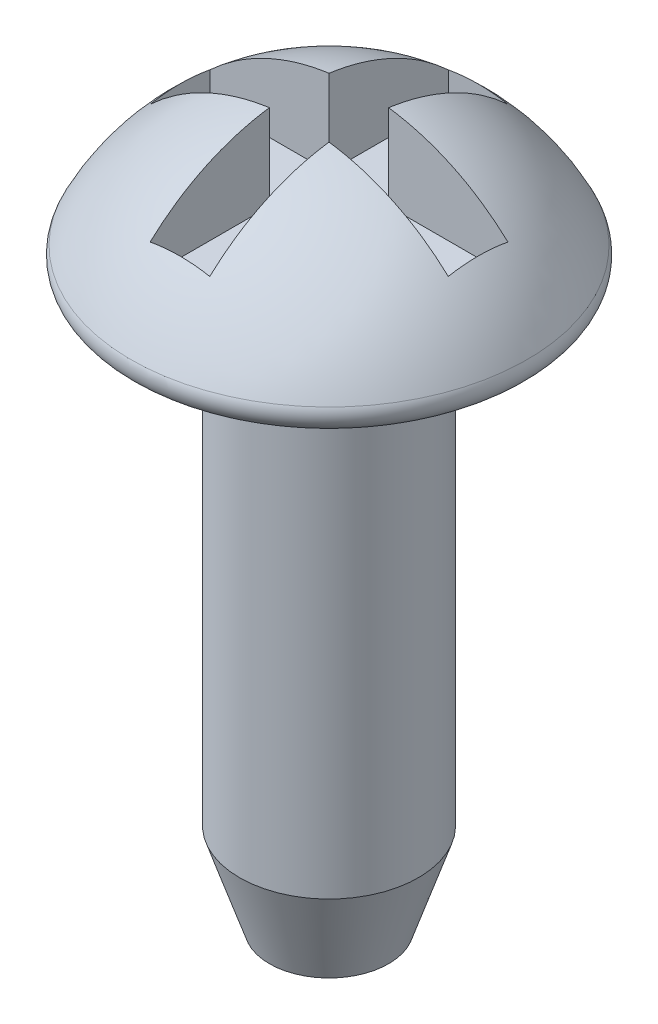
SolidWorks part; units mm, degrees
ref_plane "Front Plane" through (0, 0, 0) normal (0, 0, 1) x (1, 0, 0)
ref_plane "Top Plane" through (0, 0, 0) normal (0, 1, 0) x (1, 0, 0)
ref_plane "Right Plane" through (0, 0, 0) normal (1, 0, 0) x (0, 0, -1)
sketch "Sketch1" plane through (0, 0, 0) normal (0, 0, 1) x (1, 0, 0)
  line L0 (-1.5, 0) -> (-1.5, -8)
  line L1 (3.575, 0) -> (-3.575, 0) construction
  line L2 (-1.5, -8) -> (-1, -9.5)
  line L3 (-1, -9.5) -> (0, -9.5)
  line L4 (0, -3.575) -> (0, 3.575) construction
  line L5 (0, -2.514) -> (0, -4.9556) construction
  line L6 (0, -9.5) -> (0, 2.5)
  line L7 (-1.5, 0) -> (-3.5, 0)
  arc A0 (-3.5, 0) -> (0, 2.5) centre (0, -1.2) cw
  dimension "D1" = 1.5
  dimension "D2" = 1
  dimension "D3" = 9.5
  dimension "D4" = 8
  dimension "D5" = 3.5
  dimension "D6" = 2.5
revolve "Revolve1" add sketch "Sketch1" angle 360 about L5
fillet "Fillet1" radius 0.3 1 edges at (0, 0, 3.5)
sketch "Sketch2" plane through (0, 0, 0) normal (0, 1, 0) x (1, 0, 0)
  line L0 (0.5, 0.5) -> (2.5, 0.5)
  line L1 (-0.5, 2.5) -> (0.5, 2.5)
  line L2 (-0.5, 2.5) -> (-0.5, 0.5)
  line L3 (-0.5, -2.5) -> (0.5, -2.5)
  line L4 (0.5, 2.5) -> (0.5, 0.5)
  line L5 (-2.5, 0.5) -> (-0.5, 0.5)
  line L6 (-2.5, 0.5) -> (-2.5, -0.5)
  line L7 (-2.5, -0.5) -> (-0.5, -0.5)
  line L8 (2.5, 0.5) -> (2.5, -0.5)
  line L9 (-0.5, -0.5) -> (-0.5, -2.5)
  line L10 (0.5, -0.5) -> (2.5, -0.5)
  line L11 (0.5, -0.5) -> (0.5, -2.5)
  line L12 (-2.5, -0.5) -> (2.5, 0.5) construction
  line L13 (-0.5, 2.5) -> (0.5, -2.5) construction
  line L14 (-3.6864, 0) -> (3.6864, 0) construction
  dimension "D1" = 1
  dimension "D2" = 2.5
extrude "Cut-Extrude1" cut sketch "Sketch2" along normal through all from offset 1
